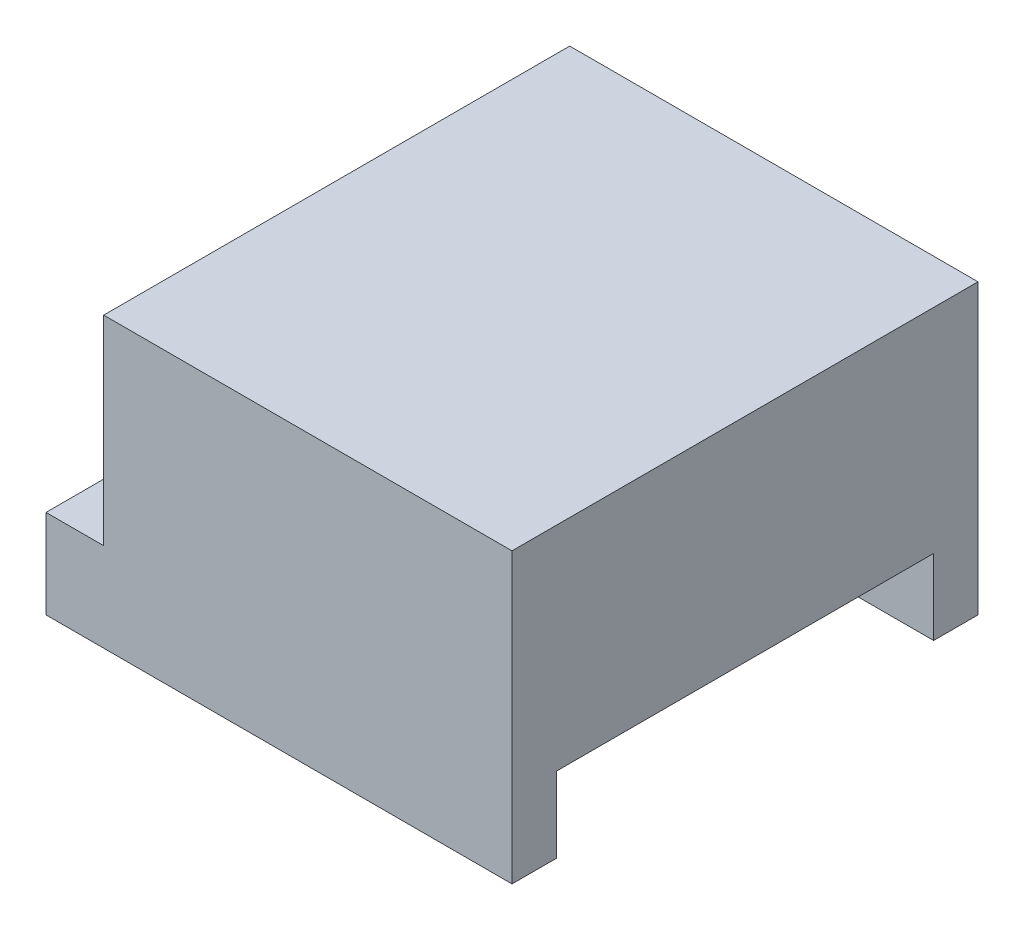
SolidWorks part; units mm, degrees
ref_plane "Front Plane" through (0, 0, 0) normal (0, 0, 1) x (1, 0, 0)
ref_plane "Top Plane" through (0, 0, 0) normal (0, 1, 0) x (1, 0, 0)
ref_plane "Right Plane" through (0, 0, 0) normal (1, 0, 0) x (0, 0, -1)
sketch "Sketch1" plane through (0, 0, 0) normal (0, 1, 0) x (1, 0, 0)
  line L1 (-46, 52.5) -> (46, 52.5)
  line L2 (-46, 52.5) -> (-46, -52.5)
  line L3 (-46, -52.5) -> (46, -52.5)
  line L4 (46, 52.5) -> (46, -52.5)
  line L5 (-46, 52.5) -> (46, -52.5) construction
  line L6 (-46, -52.5) -> (46, 52.5) construction
  point P0 (0, 0)
  dimension "D1" = 92
  dimension "D2" = 105
extrude "Boss-Extrude1" add sketch "Sketch1" along normal blind 45
sketch "Sketch2" plane through (0, 0, 0) normal (0, -1, 0) x (1, 0, 0)
  line L1 (46, -52.5) -> (-59, -52.5)
  line L2 (46, -52.5) -> (46, 52.5)
  line L3 (46, 52.5) -> (-59, 52.5)
  line L4 (-59, -52.5) -> (-59, 52.5)
  dimension "D1" = 105
extrude "Boss-Extrude2" add sketch "Sketch2" along normal blind 3
sketch "Sketch3" plane through (0, -3, 0) normal (0, -1, 0) x (1, 0, 0)
  line L0 (-59, 52.5) -> (-59, -52.5) construction
  line L1 (46, 52.5) -> (-59, 52.5)
  line L2 (46, 52.5) -> (46, 42.5)
  line L3 (46, 42.5) -> (-59, 42.5)
  line L4 (-59, 52.5) -> (-59, 42.5)
  dimension "D1" = 10
extrude "Boss-Extrude3" add sketch "Sketch3" along normal blind 17
sketch "Sketch4" plane through (0, -20, 0) normal (0, -1, 0) x (-1, 0, 0)
  line L0 (-46, -52.5) -> (59, -52.5) construction
  circle A0 centre (-41.5, -47.5) radius 1.5
  circle A1 centre (38, -47.5) radius 1.5
  dimension "D1" = 3
  dimension "D3" = 4.5
  dimension "D2" = 5
  dimension "D4" = 79.5
extrude "Cut-Extrude1" cut sketch "Sketch4" against normal blind 35
mirror "Mirror1" about plane through (0, 0, 0) normal (0, 0, 1) of "Cut-Extrude1", "Boss-Extrude3"
